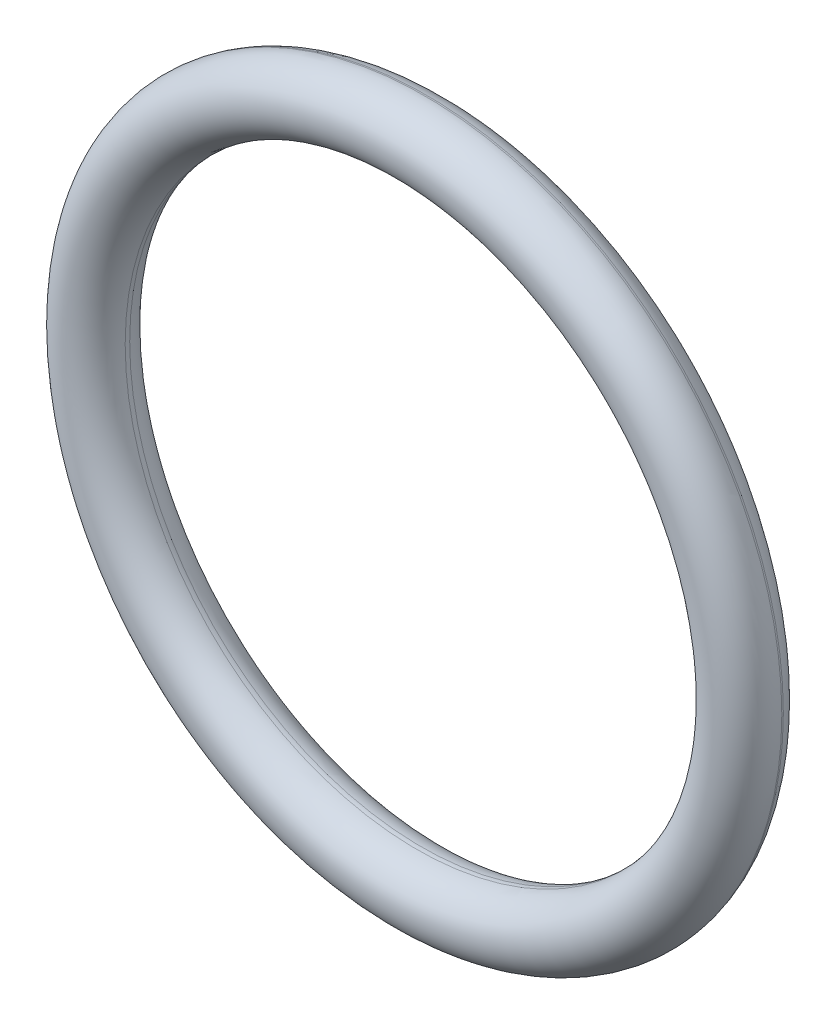
SolidWorks part; units mm, degrees
ref_plane "Plano frontal" through (0, 0, 0) normal (0, 0, 1) x (1, 0, 0)
ref_plane "Plano superior" through (0, 0, 0) normal (0, 1, 0) x (1, 0, 0)
ref_plane "Plano direito" through (0, 0, 0) normal (1, 0, 0) x (0, 0, -1)
ref_axis "Eixo1" through (0, 0, -88.99) along (0, 0, 1)
sketch "Esboço2" plane through (0, 0, 0) normal (0, 1, 0) x (1, 0, 0)
  line L0 (-5.5, 0) -> (0, 0) construction
  line L2 (-6, -0.5) -> (-6.02, -0.5)
  line L3 (-6, 0.5) -> (-6.02, 0.5)
  line L4 (-6.05, -0.47) -> (-6.05, 0.47)
  arc A0 (-6, -0.5) -> (-6, 0.5) centre (-6, 0) ccw
  arc A1 (-6.05, 0.47) -> (-6.02, 0.5) centre (-6.02, 0.47) cw
  arc A2 (-6.05, -0.47) -> (-6.02, -0.5) centre (-6.02, -0.47) ccw
  dimension "D1" = 0.03
  dimension "D2" = 5.5
sketch "Esboço3" plane through (0, 0, 0) normal (0, 1, 0) x (1, 0, 0)
  line L6 (-6, 0) -> (-5.3, 0) construction
  arc A1 (-6.1811, -0.466) -> (-6.0414, 0.4983) centre (-6, 0) ccw construction
  arc A3 (-5.3033, 0.0426) -> (-6.4821, 0.1325) centre (-5.9015, -0.0271) ccw
  arc A4 (-6.4821, 0.1325) -> (-6.4906, 0.0964) centre (-6, 0) ccw
  arc A5 (-6.4906, 0.0964) -> (-5.3, -0.0427) centre (-5.9007, -0.0195) ccw
  arc A6 (-5.3, -0.0427) -> (-5.3033, 0.0426) centre (-5.8525, -0.0214) ccw
  dimension "D1" = 0.7
revolve "Revolução1" add sketch "Esboço3" angle 360 about axis through (0, 0, -88.99) along (0, 0, 1)
